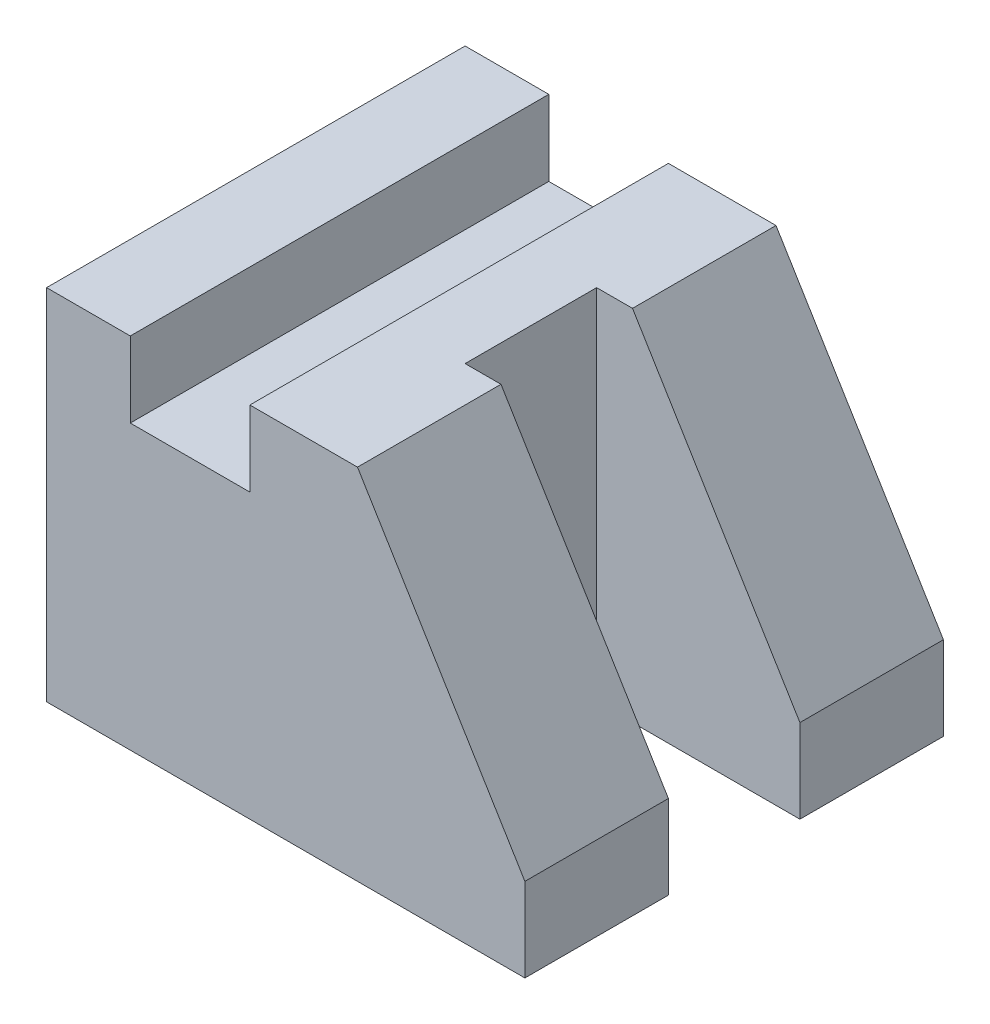
SolidWorks part; units mm, degrees
ref_plane "Ön Düzlem" through (0, 0, 0) normal (0, 0, 1) x (1, 0, 0)
ref_plane "Üst Düzlem" through (0, 0, 0) normal (0, 1, 0) x (1, 0, 0)
ref_plane "Sağ Düzlem" through (0, 0, 0) normal (1, 0, 0) x (0, 0, -1)
sketch "Çizim1" plane through (0, 0, 0) normal (0, 0, 1) x (1, 0, 0)
  line L0 (-2473.5692, 963.2462) -> (-2473.5692, -560.7538)
  line L1 (-2473.5692, -560.7538) -> (-441.5692, -560.7538)
  line L2 (-441.5692, -560.7538) -> (-441.5692, -205.1538)
  line L3 (-441.5692, -205.1538) -> (-1152.7692, 963.2462)
  line L4 (-1152.7692, 963.2462) -> (-1609.9692, 963.2462)
  line L5 (-1609.9692, 963.2462) -> (-1609.9692, 642.8154)
  line L6 (-1609.9692, 642.8154) -> (-2117.9692, 642.8154)
  line L7 (-2117.9692, 642.8154) -> (-2117.9692, 963.2462)
  line L8 (-2117.9692, 963.2462) -> (-2473.5692, 963.2462)
  dimension "D1" = 355.6
  dimension "D2" = 457.2
  dimension "D3" = 508
  dimension "D4" = 1524
  dimension "D5" = 2032
  dimension "D6" = 355.6
extrude "Yükseklik-Ekstrüzyon1" add sketch "Çizim1" along normal blind 1778
sketch "Çizim2" plane through (0, 963.2462, 0) normal (0, 1, 0) x (1, 0, 0)
  line L0 (-441.5692, -1778) -> (-1152.7692, -1778) construction
  line L1 (-1305.1692, -609.6) -> (-257.9543, -609.6)
  line L2 (-1305.1692, -609.6) -> (-1305.1692, -1168.4)
  line L3 (-1305.1692, -1168.4) -> (-257.9543, -1168.4)
  line L4 (-257.9543, -609.6) -> (-257.9543, -1168.4)
  line L5 (-441.5692, 0) -> (-1152.7692, 0) construction
  line L6 (-1152.7692, -1778) -> (-1152.7692, 0) construction
  dimension "D1" = 609.6
  dimension "D2" = 609.6
  dimension "D3" = 152.4
extrude "Kes-Ekstrüzyon2" cut sketch "Çizim2" against normal blind 1778
